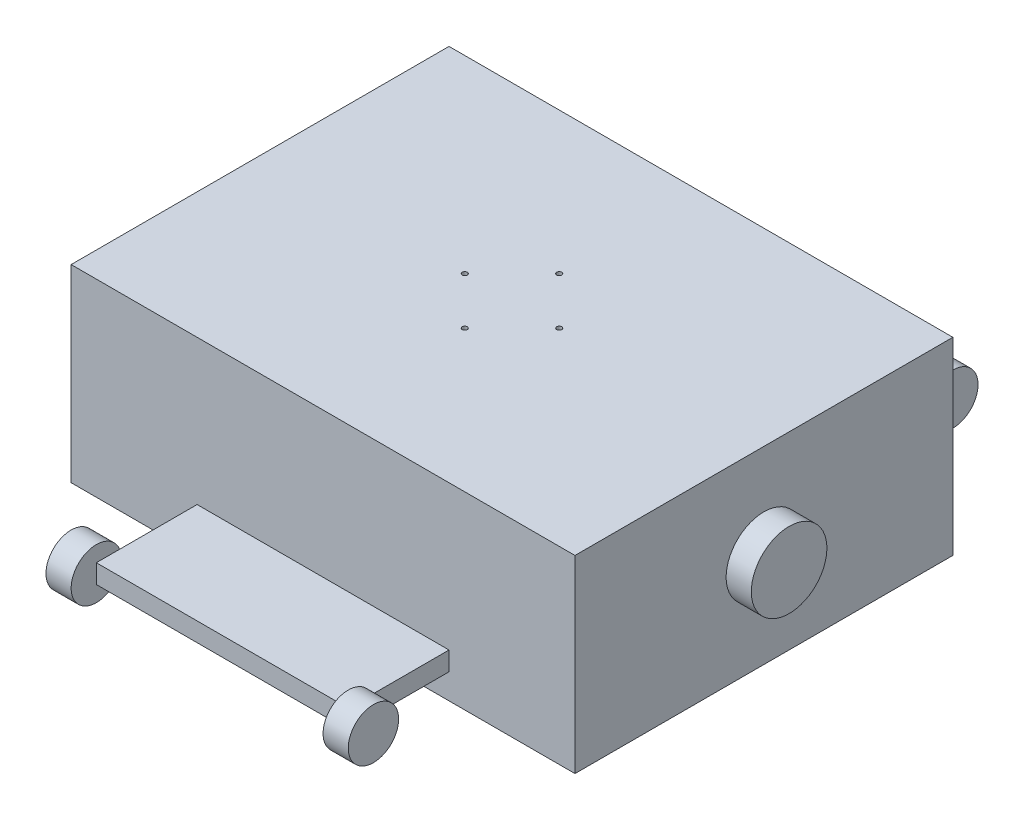
SolidWorks part; units mm, degrees
ref_plane "前视基准面" through (0, 0, 0) normal (0, 0, 1) x (1, 0, 0)
ref_plane "上视基准面" through (0, 0, 0) normal (0, 1, 0) x (1, 0, 0)
ref_plane "右视基准面" through (0, 0, 0) normal (1, 0, 0) x (0, 0, -1)
sketch "草图1" plane through (0, 0, 0) normal (0, 0, 1) x (1, 0, 0)
  line L1 (-200, 75) -> (200, 75)
  line L2 (-200, 75) -> (-200, -75)
  line L3 (-200, -75) -> (200, -75)
  line L4 (200, 75) -> (200, -75)
  line L5 (-200, 75) -> (200, -75) construction
  line L6 (-200, -75) -> (200, 75) construction
  point P0 (0, 0)
  dimension "D1" = 400
  dimension "D2" = 150
extrude "凸台-拉伸1" add sketch "草图1" against normal blind 300
sketch "草图2" plane through (200, 0, 0) normal (1, 0, 0) x (0, 0, -1)
  line L0 (0, 0) -> (300, 0) construction
  line L1 (300, -75) -> (300, 75) construction
  line L2 (150, -75) -> (150, 75) construction
  line L3 (300, 75) -> (0, 75) construction
  circle A2 centre (150, 0) radius 30
  point P10 (150, 0)
  dimension "D5" = 60
extrude "凸台-拉伸2" add sketch "草图2" along normal blind 20
sketch "草图5" plane through (0, 0, 0) normal (1, 0, 0) x (0, 0, -1)
  line L0 (150, 75) -> (150, -75) construction
  line L1 (300, 75) -> (0, 75) construction
  line L2 (300, -75) -> (0, -75) construction
sketch "草图6" plane through (-200, 0, 0) normal (-1, 0, 0) x (0, 0, 1)
  line L0 (-300, 0) -> (0, 0) construction
  line L1 (-300, 75) -> (-300, -75) construction
  line L2 (-150, -75) -> (-150, 75) construction
  circle A2 centre (-150, 0) radius 30
  point P9 (-150, 0)
  dimension "D1" = 60
sketch "草图8" plane through (0, 0, 0) normal (0, 0, 1) x (1, 0, 0)
  line L0 (0, 75) -> (0, -75) construction
  line L1 (100, -55) -> (-100, -55)
  line L2 (100, -55) -> (100, -40)
  line L3 (100, -40) -> (-100, -40)
  line L4 (-100, -55) -> (-100, -40)
  line L5 (100, -55) -> (-100, -40) construction
  line L6 (100, -40) -> (-100, -55) construction
  point P0 (0, -47.5)
  dimension "D1" = 200
  dimension "D2" = 15
  dimension "D3" = 40
extrude "凸台-拉伸6" add sketch "草图8" along normal blind 80
ref_plane "基准面1" through (0, 0, -150) normal (0, 0, 1) x (1, 0, 0)
mirror "镜向2" about plane through (0, 0, -150) normal (0, 0, 1) of "凸台-拉伸6"
sketch "草图9" plane through (100, 0, 0) normal (1, 0, 0) x (0, 0, -1)
  line L0 (-80, -55) -> (-80, -40) construction
  circle A0 centre (-80, -47.5) radius 20
  dimension "D1" = 40
extrude "凸台-拉伸7" add sketch "草图9" along normal blind 20
mirror "镜向3" about plane through (0, 0, -150) normal (0, 0, 1) of "凸台-拉伸7"
mirror "镜向4" about plane through (0, 0, 0) normal (1, 0, 0) of "镜向3", "凸台-拉伸7"
sketch "草图10" plane through (0, 75, 0) normal (0, 1, 0) x (1, 0, 0)
  line L0 (-200, 300) -> (200, 0) construction
  circle A0 centre (0, 150) radius 37.5 construction
  circle A1 centre (0, 187.5) radius 2
  circle A2 centre (37.5, 150) radius 2
  circle A3 centre (0, 112.5) radius 2
  circle A4 centre (-37.5, 150) radius 2
  dimension "D1" = 75
  dimension "D2" = 4
extrude "切除-拉伸1" cut sketch "草图10" against normal blind 10
extrude "凸台-拉伸8" add sketch "草图6" along normal blind 20
